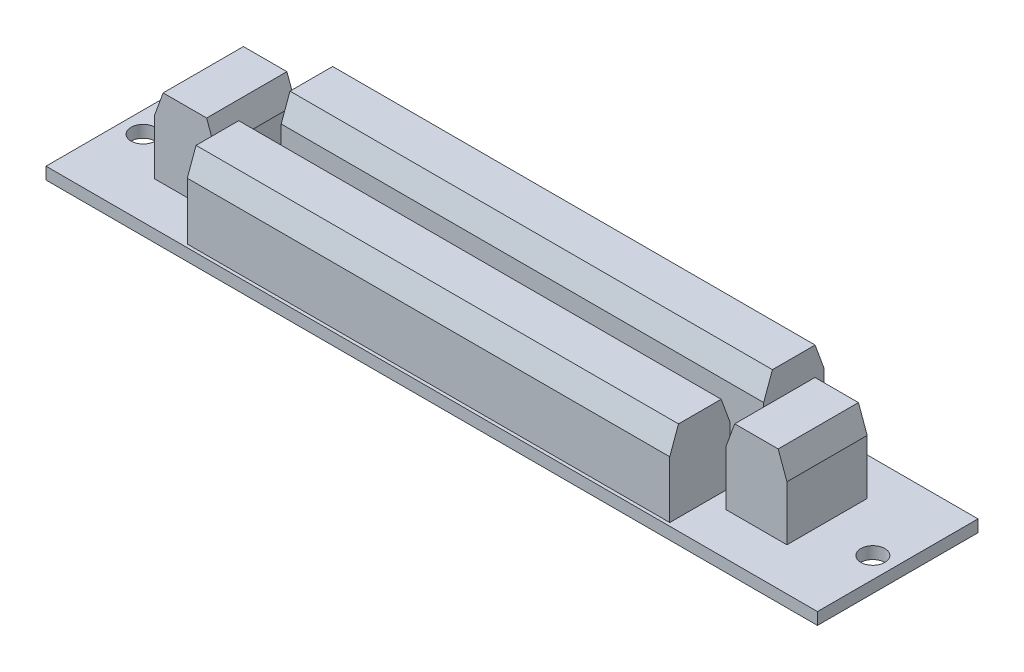
SolidWorks part; units mm, degrees
ref_plane "Front Plane" through (0, 0, 0) normal (0, 0, 1) x (1, 0, 0)
ref_plane "Top Plane" through (0, 0, 0) normal (0, 1, 0) x (1, 0, 0)
ref_plane "Right Plane" through (0, 0, 0) normal (1, 0, 0) x (0, 0, -1)
sketch "Sketch1" plane through (0, 0, 0) normal (0, 1, 0) x (1, 0, 0)
  line L1 (0, 0) -> (96.1, 0)
  line L2 (0, 0) -> (0, 20)
  line L3 (0, 20) -> (96.1, 20)
  line L4 (96.1, 0) -> (96.1, 20)
  circle A0 centre (2.6, 9.5) radius 1.5
  circle A1 centre (93.5, 9.5) radius 1.5
  point P9 (0, 0)
  dimension "D3" = 3
  dimension "D4" = 3
  dimension "D1" = 20
  dimension "D2" = 96.1
  dimension "D5" = 9.5
  dimension "D6" = 2.6
  dimension "D7" = 2.6
extrude "Boss-Extrude1" add sketch "Sketch1" along normal blind 1.5
sketch "Sketch2" plane through (0, 1.5, 0) normal (0, 1, 0) x (1, 0, 0)
  line L0 (96.1, 0) -> (96.1, 20) construction
  line L1 (17.2, 7.9) -> (77.3, 7.9)
  line L2 (17.2, 7.9) -> (17.2, 0.4)
  line L3 (17.2, 0.4) -> (77.3, 0.4)
  line L4 (77.3, 7.9) -> (77.3, 0.4)
  line L5 (0, 0) -> (96.1, 0) construction
  dimension "D1" = 60.1
  dimension "D2" = 7.5
  dimension "D3" = 18.8
  dimension "D4" = 0.4
extrude "Boss-Extrude2" add sketch "Sketch2" along normal blind 10.1
chamfer "Chamfer1" distance 3 angle 20 2 edges at (47.25, 11.6, -7.9) (47.25, 11.6, -0.4)
ref_plane "Plane1" through (0, 0, -10) normal (0, 0, 1) x (1, 0, 0)
mirror "Mirror1" about plane through (0, 0, -10) normal (0, 0, 1) of "Chamfer1", "Boss-Extrude2"
sketch "Sketch3" plane through (0, 1.5, 0) normal (0, 1, 0) x (1, 0, 0)
  line L0 (0, 20) -> (0, 0) construction
  line L1 (8.1, 15.4) -> (15.7, 15.4)
  line L2 (8.1, 15.4) -> (8.1, 5.4)
  line L3 (8.1, 5.4) -> (15.7, 5.4)
  line L4 (15.7, 15.4) -> (15.7, 5.4)
  line L5 (79.4, 15.3) -> (87, 15.3)
  line L6 (79.4, 15.3) -> (79.4, 5.3)
  line L7 (79.4, 5.3) -> (87, 5.3)
  line L8 (87, 15.3) -> (87, 5.3)
  line L9 (96.1, 20) -> (0, 20) construction
  line L10 (96.1, 0) -> (96.1, 20) construction
  dimension "D1" = 10
  dimension "D2" = 7.6
  dimension "D3" = 10
  dimension "D4" = 7.6
  dimension "D5" = 8.1
  dimension "D6" = 4.6
  dimension "D7" = 4.7
  dimension "D8" = 9.1
extrude "Boss-Extrude3" add sketch "Sketch3" along normal blind 9.8
chamfer "Chamfer2" distance 3 angle 20 4 edges at (15.7, 11.3, -10.4) (8.1, 11.3, -10.4) (87, 11.3, -10.3) (79.4, 11.3, -10.3)
